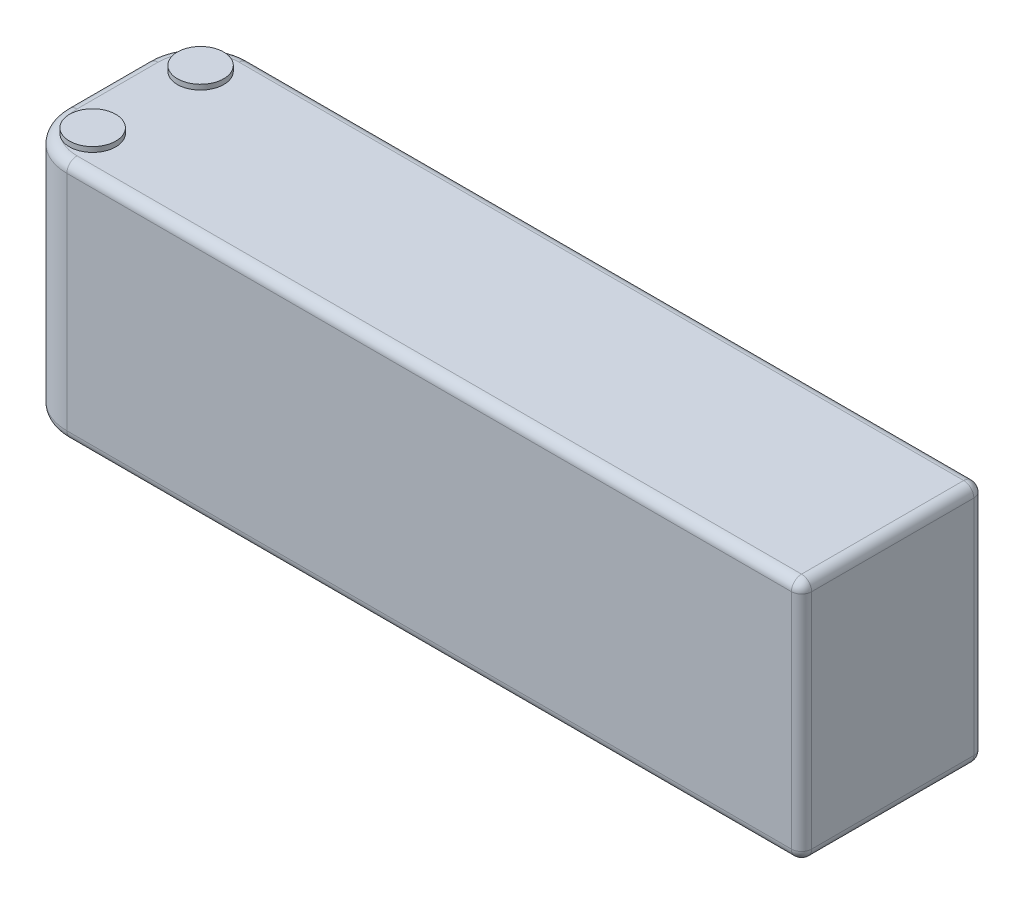
SolidWorks part; units mm, degrees
ref_plane "Front Plane" through (0, 0, 0) normal (0, 0, 1) x (1, 0, 0)
ref_plane "Top Plane" through (0, 0, 0) normal (0, 1, 0) x (1, 0, 0)
ref_plane "Right Plane" through (0, 0, 0) normal (1, 0, 0) x (0, 0, -1)
sketch "Sketch3" plane through (0, 0, 0) normal (0, 1, 0) x (1, 0, 0)
  line L0 (10, 0) -> (155, 0)
  line L1 (155, 0) -> (155, 36)
  line L2 (155, 36) -> (10, 36)
  line L3 (0, 26) -> (0, 10)
  arc A0 (10, 36) -> (0, 26) centre (10, 26) ccw
  arc A1 (10, 0) -> (0, 10) centre (10, 10) cw
  point P10 (0, 0)
  dimension "D1" = 10
extrude "Boss-Extrude1" add sketch "Sketch3" along normal blind 48
fillet "Fillet1" radius 2 14 edges at (82.5, 48, -36) (82.5, 0, 0) (155, 24, -36) (155, 0, -18) (82.5, 48, 0) (82.5, 0, -36) (155, 48, -18) (155, 24, 0) (2.9289, 48, -33.0711) (0, 48, -18) (2.9289, 48, -2.9289) (2.9289, 0, -2.9289) (0, 0, -18) (2.9289, 0, -33.0711)
ref_plane "Plane1" through (0, 24, 0) normal (0, 1, 0) x (1, 0, 0)
sketch "Sketch7" plane through (0, 48, 0) normal (0, 1, 0) x (1, 0, 0)
  line L0 (0, 18) -> (18.781, 18) construction
  line L1 (0, 10) -> (0, 26) construction
  circle A1 centre (7.7381, 28.6509) radius 4.5727
  circle A2 centre (7.7381, 7.3491) radius 4.5727
extrude "Boss-Extrude3" add sketch "Sketch7" along normal blind 1
scale "Ölçek1" scale about centroid uniform scaling yes scale factor 0.5
